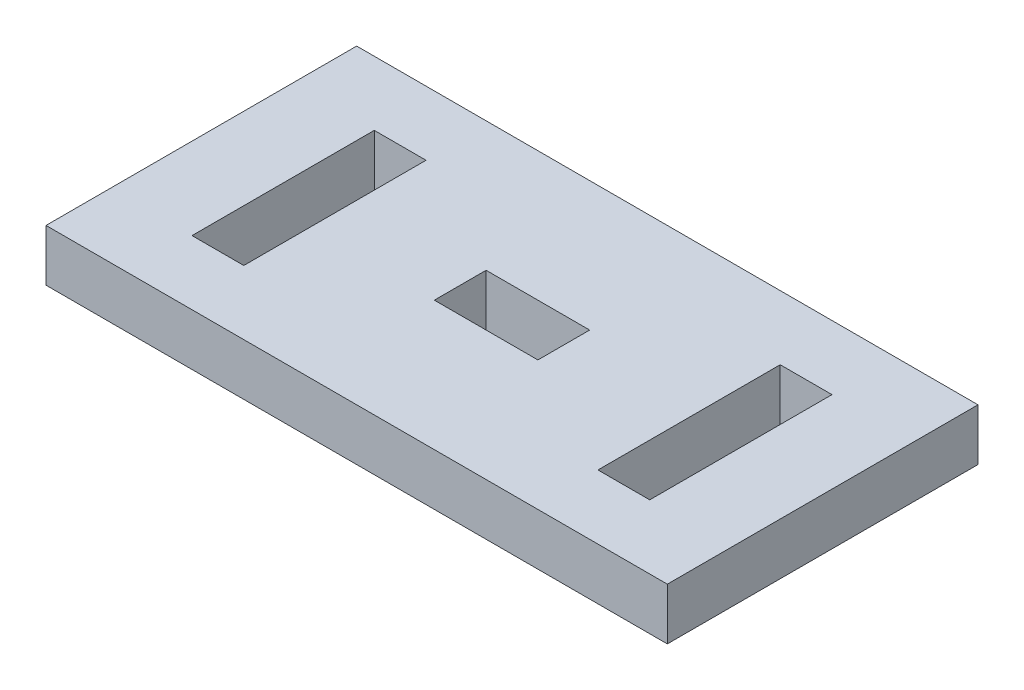
SolidWorks part; units mm, degrees
ref_plane "Front Plane" through (0, 0, 0) normal (0, 0, 1) x (1, 0, 0)
ref_plane "Top Plane" through (0, 0, 0) normal (0, 1, 0) x (1, 0, 0)
ref_plane "Right Plane" through (0, 0, 0) normal (1, 0, 0) x (0, 0, -1)
sketch "Sketch1" plane through (0, 0, 0) normal (0, 1, 0) x (1, 0, 0)
  line L0 (38.1, 38.1) -> (38.1, 0) construction
  line L1 (0, 0) -> (76.2, 0)
  line L2 (0, 0) -> (0, 38.1)
  line L3 (0, 38.1) -> (76.2, 38.1)
  line L4 (76.2, 0) -> (76.2, 38.1)
  line L5 (10.033, 19.05) -> (66.167, 19.05) construction
  line L6 (10.033, 30.226) -> (10.033, 7.874)
  line L7 (10.033, 30.226) -> (16.383, 30.226)
  line L8 (10.033, 7.874) -> (16.383, 7.874)
  line L9 (16.383, 30.226) -> (16.383, 7.874)
  line L10 (66.167, 7.874) -> (59.817, 7.874)
  line L11 (59.817, 30.226) -> (59.817, 7.874)
  line L12 (66.167, 30.226) -> (59.817, 30.226)
  line L13 (66.167, 30.226) -> (66.167, 7.874)
  line L15 (31.75, 15.875) -> (44.45, 15.875)
  line L16 (31.75, 15.875) -> (31.75, 22.225)
  line L17 (31.75, 22.225) -> (44.45, 22.225)
  line L18 (44.45, 15.875) -> (44.45, 22.225)
  line L19 (31.75, 15.875) -> (44.45, 22.225) construction
  line L20 (31.75, 22.225) -> (44.45, 15.875) construction
  point P9 (38.1, 19.05)
  point P10 (10.033, 19.05)
  point P19 (38.1, 19.05)
  dimension "D1" = 76.2
  dimension "D2" = 38.1
  dimension "D3" = 56.134
  dimension "D4" = 6.35
  dimension "D5" = 22.352
  dimension "D6" = 6.35
  dimension "D7" = 12.7
extrude "Boss-Extrude1" add sketch "Sketch1" along normal blind 6.35
